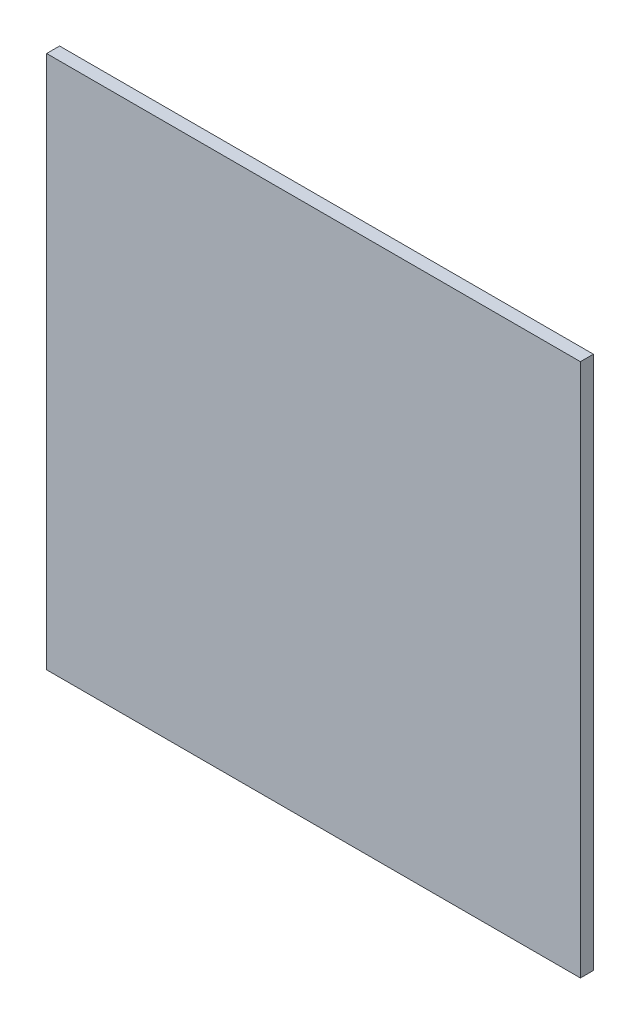
SolidWorks part; units mm, degrees
material "OSB_Plywood"
ref_plane "Front Plane" through (0, 0, 0) normal (0, 0, 1) x (1, 0, 0)
ref_plane "Top Plane" through (0, 0, 0) normal (0, 1, 0) x (1, 0, 0)
ref_plane "Right Plane" through (0, 0, 0) normal (1, 0, 0) x (0, 0, -1)
sketch "Sketch1" plane through (0, 0, 0) normal (0, 0, 1) x (1, 0, 0)
  line L1 (0, 0) -> (457.2, 0)
  line L2 (0, 0) -> (0, 457.2)
  line L3 (0, 457.2) -> (457.2, 457.2)
  line L4 (457.2, 0) -> (457.2, 457.2)
  dimension "D1" = 457.2
  dimension "D2" = 457.2
extrude "Boss-Extrude1" add sketch "Sketch1" along normal blind 11.1125
